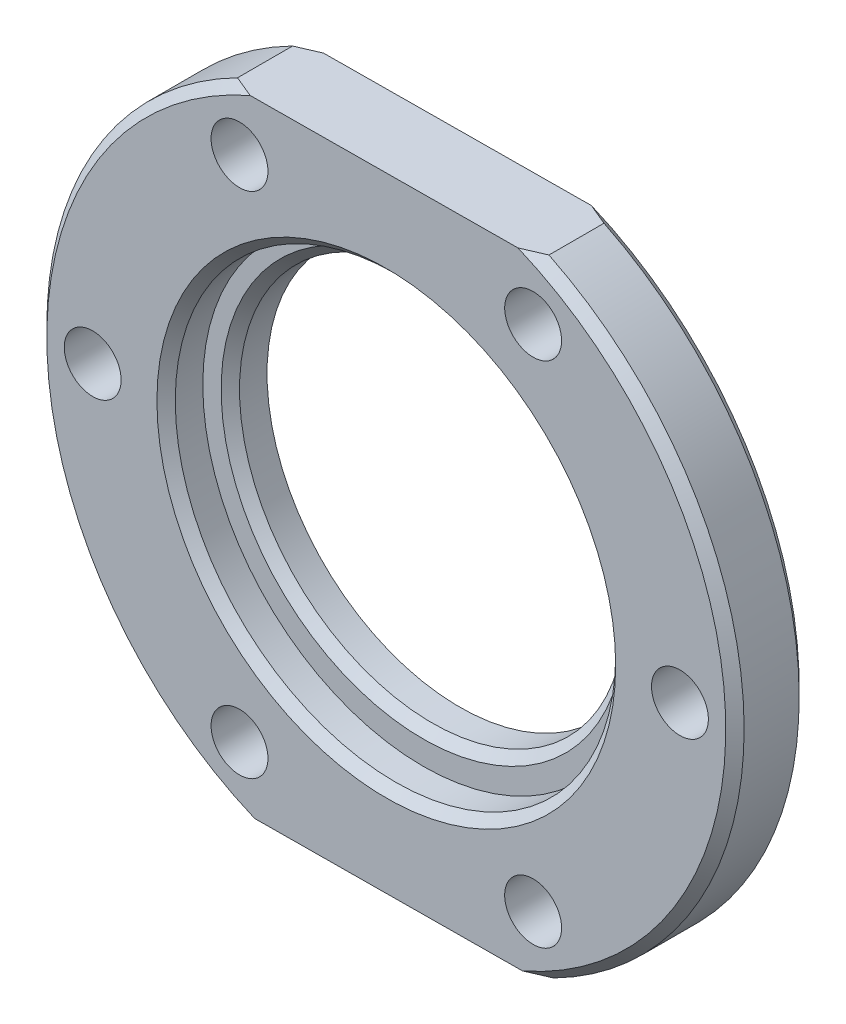
SolidWorks part; units mm, degrees
ref_plane "Front Plane" through (0, 0, 0) normal (0, 0, 1) x (1, 0, 0)
ref_plane "Top Plane" through (0, 0, 0) normal (0, 1, 0) x (1, 0, 0)
ref_plane "Right Plane" through (0, 0, 0) normal (1, 0, 0) x (0, 0, -1)
sketch "Sketch2" plane through (0, 0, 0) normal (0, 0, 1) x (1, 0, 0)
  line L0 (-8.6068, 16.9388) -> (8.3633, 17.0603)
  line L1 (-8.3633, -17.0603) -> (8.6068, -16.9388)
  arc A0 (-8.6068, 16.9388) -> (-8.3633, -17.0603) centre (0, 0) ccw
  circle A1 centre (0, 0) radius 16 construction
  circle A2 centre (0, 0.2898) radius 10.5
  circle A3 centre (-16, 0) radius 1.55
  circle A4 centre (0, 0) radius 16 construction
  circle A5 centre (0, 0) radius 16 construction
  circle A6 centre (0, 0) radius 16 construction
  circle A7 centre (0, 0) radius 16 construction
  circle A8 centre (0, 0) radius 16 construction
  circle A9 centre (0.0005, 0.0009) radius 16 construction
  circle A10 centre (-7.9995, 13.8573) radius 1.55
  circle A11 centre (0.0015, 0.0009) radius 16 construction
  circle A12 centre (8.0015, 13.8573) radius 1.55
  circle A13 centre (0.002, 0) radius 16 construction
  circle A14 centre (16.002, 0) radius 1.55
  circle A15 centre (0.0015, -0.0009) radius 16 construction
  circle A16 centre (8.0015, -13.8573) radius 1.55
  circle A17 centre (0.0005, -0.0009) radius 16 construction
  circle A18 centre (-7.9995, -13.8573) radius 1.55
  arc A19 (8.6068, -16.9388) -> (8.3633, 17.0603) centre (0, 0) ccw
  point P21 (0, 0)
  point P42 (0.001, 0)
  dimension "D1" = 38
  dimension "D2" = 32
  dimension "D3" = 21
  dimension "D4" = 3.1
  dimension "D7" = 17
  dimension "D8" = 17
  dimension "D5" = 6
  dimension "D6" = 6
extrude "Boss-Extrude1" add sketch "Sketch2" along normal blind 4
sketch "Sketch3" plane through (0, 0, 4) normal (0, 0, 1) x (1, 0, 0)
  circle A0 centre (0, 0) radius 12
  dimension "D1" = 24
extrude "Cut-Extrude1" cut sketch "Sketch3" against normal blind 2
chamfer "Chamfer1" distance 0.5 angle 45 10 edges at (10.5, 0.2898, 2) (0.1217, -16.9996, 0) (-18.9995, -0.136, 0) (-0.1217, 16.9996, 0) (18.9995, 0.136, 0) (-0.1217, 16.9996, 4) (18.9995, 0.136, 4) (0.1217, -16.9996, 4) (-18.9995, -0.136, 4) (12, 0, 4)
